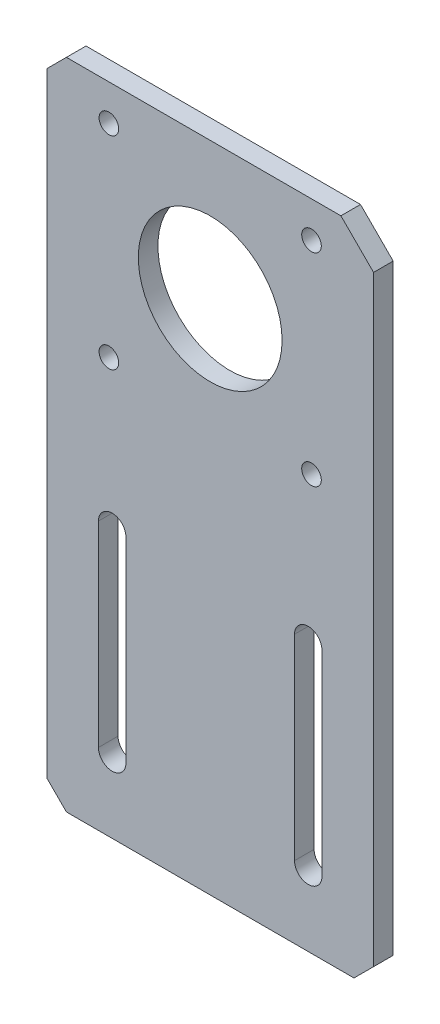
SolidWorks part; units mm, degrees
ref_plane "前视基准面" through (0, 0, 0) normal (0, 0, 1) x (1, 0, 0)
ref_plane "上视基准面" through (0, 0, 0) normal (0, 1, 0) x (1, 0, 0)
ref_plane "右视基准面" through (0, 0, 0) normal (1, 0, 0) x (0, 0, -1)
sketch "草图1" plane through (0, 0, 0) normal (0, 0, 1) x (1, 0, 0)
  line L0 (25, 0) -> (25, -100) construction
  line L1 (0, 0) -> (45, 0)
  line L2 (0, 0) -> (0, -100)
  line L3 (0, -100) -> (50, -100)
  line L4 (50, -5) -> (50, -100)
  line L5 (25, -21) -> (0, -21) construction
  line L6 (45, 0) -> (50, -5)
  line L7 (10, -59) -> (10, -89) construction
  line L8 (7.9, -59) -> (7.9, -89)
  line L9 (12.1, -59) -> (12.1, -89)
  line L10 (7.9, -59) -> (7.9, -89)
  line L11 (12.1, -59) -> (12.1, -89)
  line L12 (7.9, -59) -> (7.9, -89)
  line L13 (12.1, -59) -> (12.1, -89)
  line L14 (7.9, -59) -> (7.9, -89)
  line L15 (12.1, -59) -> (12.1, -89)
  line L16 (40, -59) -> (40, -89) construction
  line L17 (37.9, -59) -> (37.9, -89)
  line L18 (42.1, -59) -> (42.1, -89)
  line L19 (37.9, -59) -> (37.9, -89)
  line L20 (42.1, -59) -> (42.1, -89)
  line L21 (37.9, -59) -> (37.9, -89)
  line L22 (42.1, -59) -> (42.1, -89)
  line L23 (37.9, -59) -> (37.9, -89)
  line L24 (42.1, -59) -> (42.1, -89)
  circle A0 centre (25, -21) radius 11
  circle A1 centre (9.5, -5.5) radius 1.5
  circle A2 centre (9.5, -36.5) radius 1.5
  circle A3 centre (40.5, -36.5) radius 1.5
  circle A4 centre (40.5, -5.5) radius 1.5
  arc A5 (7.9, -59) -> (12.1, -59) centre (10, -59) cw
  arc A6 (7.9, -89) -> (12.1, -89) centre (10, -89) ccw
  arc A7 (42.1, -89) -> (37.9, -89) centre (40, -89) cw
  arc A8 (42.1, -59) -> (37.9, -59) centre (40, -59) ccw
  point P3 (50, 0)
  dimension "D3" = 22
  dimension "D4" = 25
  dimension "D5" = 21
  dimension "D6" = 3
  dimension "D7" = 15.5
  dimension "D8" = 15.5
  dimension "D1" = 50
  dimension "D2" = 100
  dimension "D9" = 15
  dimension "D10" = 30
  dimension "D12" = 11
  dimension "D13" = 2.1
  dimension "D14" = 2.1
extrude "凸台-拉伸1" add sketch "草图1" along normal blind 3 contours L6 L1 L2 L3 L4 A8 L18 A7 L17 A6 L8 A5 L9 A2 A1 A0 A3 A4
chamfer "倒角1" distance 3 angle 45 3 edges at (0, -100, 1.5) (50, -100, 1.5) (0, 0, 1.5)
